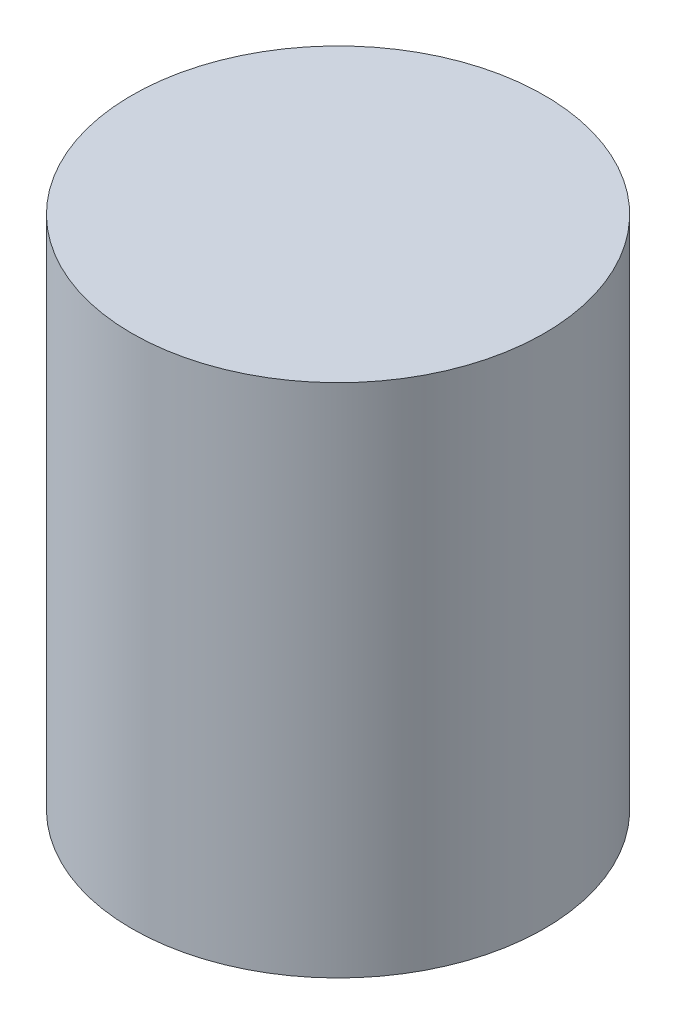
SolidWorks part; units mm, degrees
ref_plane "Front Plane" through (0, 0, 0) normal (0, 0, 1) x (1, 0, 0)
ref_plane "Top Plane" through (0, 0, 0) normal (0, 1, 0) x (1, 0, 0)
ref_plane "Right Plane" through (0, 0, 0) normal (1, 0, 0) x (0, 0, -1)
sketch "Sketch1" plane through (0, 0, 0) normal (0, 1, 0) x (1, 0, 0)
  circle A0 centre (0, 0) radius 400
  point P0 (0, 0)
  point P1 (0, 0)
  dimension "D3" = 800
extrude "Boss-Extrude2" add sketch "Sketch1" along normal mid plane 1000
